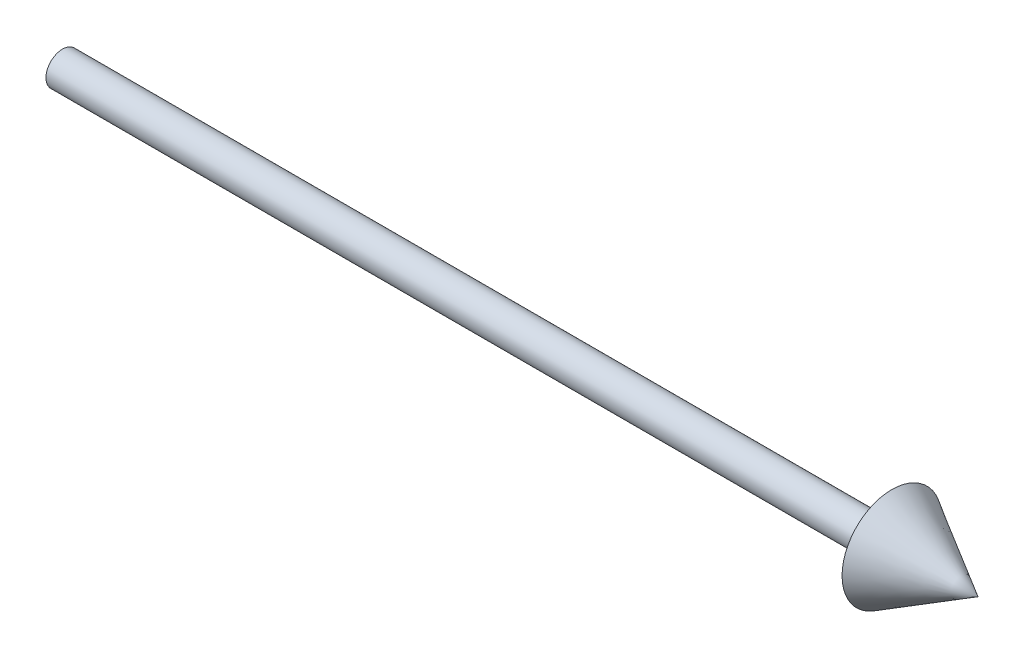
SolidWorks part; units mm, degrees
ref_plane "Front Plane" through (0, 0, 0) normal (0, 0, 1) x (1, 0, 0)
ref_plane "Top Plane" through (0, 0, 0) normal (0, 1, 0) x (1, 0, 0)
ref_plane "Right Plane" through (0, 0, 0) normal (1, 0, 0) x (0, 0, -1)
sketch "Sketch1" plane through (0, 0, 0) normal (1, 0, 0) x (0, 0, -1)
  circle A0 centre (0, 0) radius 1
  dimension "D1" = 2
extrude "Boss-Extrude1" add sketch "Sketch1" along normal blind 50
sketch "Sketch4" plane through (0, 0, 0) normal (0, 1, 0) x (1, 0, 0)
  line L0 (50, 0) -> (50, 3)
  line L1 (50, -1) -> (50, 1) construction
  line L2 (50, 3) -> (55.1962, 0)
  line L3 (50, 0) -> (55.1962, 0)
  dimension "D1" = 3
  dimension "D2" = 60
revolve "Revolve1" add sketch "Sketch4" angle 360 about L3
